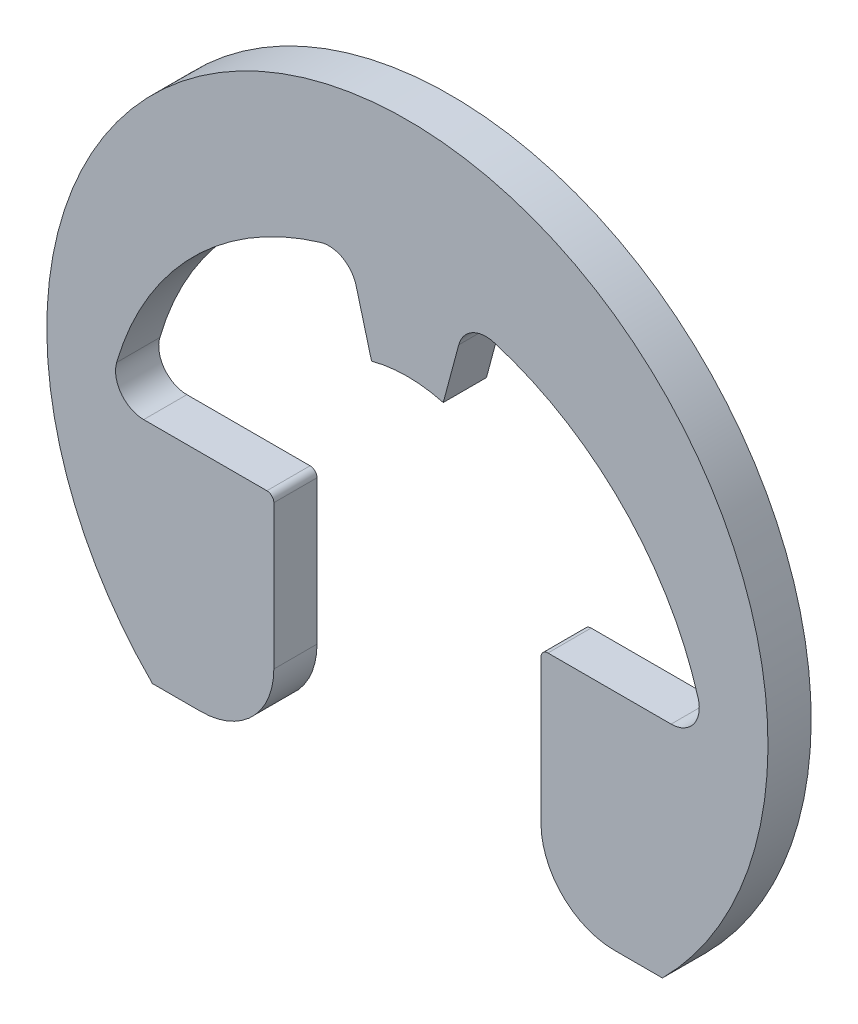
SolidWorks part; units mm, degrees
ref_plane "Plane1" through (0, 0, 0) normal (0, 0, 1) x (1, 0, 0)
ref_plane "Plane2" through (0, 0, 0) normal (0, 1, 0) x (1, 0, 0)
ref_plane "Plane3" through (0, 0, 0) normal (1, 0, 0) x (0, 0, -1)
sketch "Clipboard" plane through (0, 0, 0) normal (0, 0, 1) x (1, 0, 0)
  line L0 (0, 0) -> (1.9, 0)
  circle A0 centre (0, 0) radius 1.825
  circle A1 centre (0, 0) radius 4.75
  dimension "FreeID" = 3.65
  dimension "FreeOD" = 9.5
  dimension "LargeSection" = 1.9
sketch "BodySke" plane through (0, 0, 0) normal (0, 0, 1) x (1, 0, 0)
  line L0 (-4.0603, 0) -> (4.0603, 0) construction
  line L1 (0, 0) -> (0, 3.1103) construction
  line L2 (0, 0) -> (0.1962, 0.7323) construction
  line L3 (0, 0) -> (4.8396, -1.2968) construction
  line L4 (0, 0) -> (-0.1962, 0.7323) construction
  line L5 (0, 0) -> (-4.8396, -1.2968) construction
  line L6 (0, 0) -> (3.5428, -3.5428) construction
  line L7 (0, 0) -> (-3.5428, -3.5428) construction
  line L8 (3.5428, -3.5428) -> (2.8743, -3.5428)
  line L9 (-2.8743, -3.5428) -> (-3.5428, -3.5428)
  line L10 (1.9524, -0.4269) -> (3.6642, -0.4269)
  line L11 (0.713, 2.6611) -> (0.4982, 1.8594)
  line L12 (-0.713, 2.6611) -> (-0.4982, 1.8594)
  line L13 (1.8561, -0.5231) -> (1.8561, -2.5247)
  line L14 (-1.9524, -0.4269) -> (-3.6642, -0.4269)
  line L15 (-1.8561, -0.5231) -> (-1.8561, -2.5247)
  circle A0 centre (0, 0) radius 1.925 construction
  arc A1 (4.0603, 0) -> (-4.0603, 0) centre (0, -1.0951) ccw construction
  arc A2 (3.5428, -3.5428) -> (-3.5428, -3.5428) centre (0, 0) ccw
  arc A3 (1.9524, -0.4269) -> (1.8561, -0.5231) centre (1.9524, -0.5231) ccw
  arc A4 (-1.8561, -0.5231) -> (-1.9524, -0.4269) centre (-1.9524, -0.5231) ccw
  arc A5 (-4.0399, 0.0729) -> (-1.2027, 2.9346) centre (0, -1.0951) cw
  arc A6 (-0.4982, 1.8594) -> (0.4982, 1.8594) centre (0, 0) cw
  arc A7 (1.2027, 2.9346) -> (4.0399, 0.0729) centre (0, -1.0951) cw
  arc A8 (3.6642, -0.4269) -> (4.0399, 0.0729) centre (3.6642, -0.0357) ccw
  arc A9 (1.2027, 2.9346) -> (0.713, 2.6611) centre (1.0908, 2.5598) ccw
  arc A10 (-0.713, 2.6611) -> (-1.2027, 2.9346) centre (-1.0908, 2.5598) ccw
  arc A11 (-4.0399, 0.0729) -> (-3.6642, -0.4269) centre (-3.6642, -0.0357) ccw
  arc A12 (1.8561, -2.5247) -> (2.8743, -3.5428) centre (2.8743, -2.5247) ccw
  arc A13 (-2.8743, -3.5428) -> (-1.8561, -2.5247) centre (-2.8743, -2.5247) ccw
  dimension "D1" = 15
  dimension "GrooveDia" = 3.85
  dimension "OutsideDia" = 10.0205
  dimension "D3" = 30
  dimension "CavityFilletRad" = 0.3911
  dimension "InnerTipRad" = 0.0963
  dimension "OuterTipRadius" = 1.0181
  dimension "CavityWidth" = 8.1205
  dimension "CavityHeight" = 3.1103
extrude "Body" add sketch "BodySke" against normal blind 0.6
equation "' \"FreeID@Clipboard\" = 2.9"
equation "' \"Thickness@Body\" = 0.6"
equation "' \"GrooveDia@BodySke\" = 3.0"
equation "' \"FreeOD@Clipboard\" = 8.5"
equation "' \"LargeSection@Clipboard\" = 1.5"
equation "' \"FreeID@Clipboard\" = 11.5"
equation "' \"Thickness@Body\" = 1.1"
equation "' \"GrooveDia@BodySke\" = 11.8"
equation "' \"FreeOD@Clipboard\" = 23.2"
equation "' \"LargeSection@Clipboard\" = 3.9"
equation "\"OutsideDia@BodySke\" = ( \"GrooveDia@BodySke\"  /  \"FreeID@Clipboard\" )  * \"FreeOD@Clipboard\""
equation "\"CavityHeight@BodySke\" = \"OutsideDia@BodySke\"  /  2 - \"LargeSection@Clipboard\""
equation "\"CavityWidth@BodySke\" = \"OutsideDia@BodySke\" -  \"LargeSection@Clipboard\""
equation "\"CavityFilletRad@BodySke\" =  (\"CavityHeight@BodySke\" * 2 - \"GrooveDia@BodySke\") / 2 * 0.33"
equation "\"InnerTipRad@BodySke\" = \"GrooveDia@BodySke\" * 0.025"
equation "\"OuterTipRadius@BodySke\" =  (\"OutsideDia@BodySke\" - \"GrooveDia@BodySke\") / 2 * 0.33"
